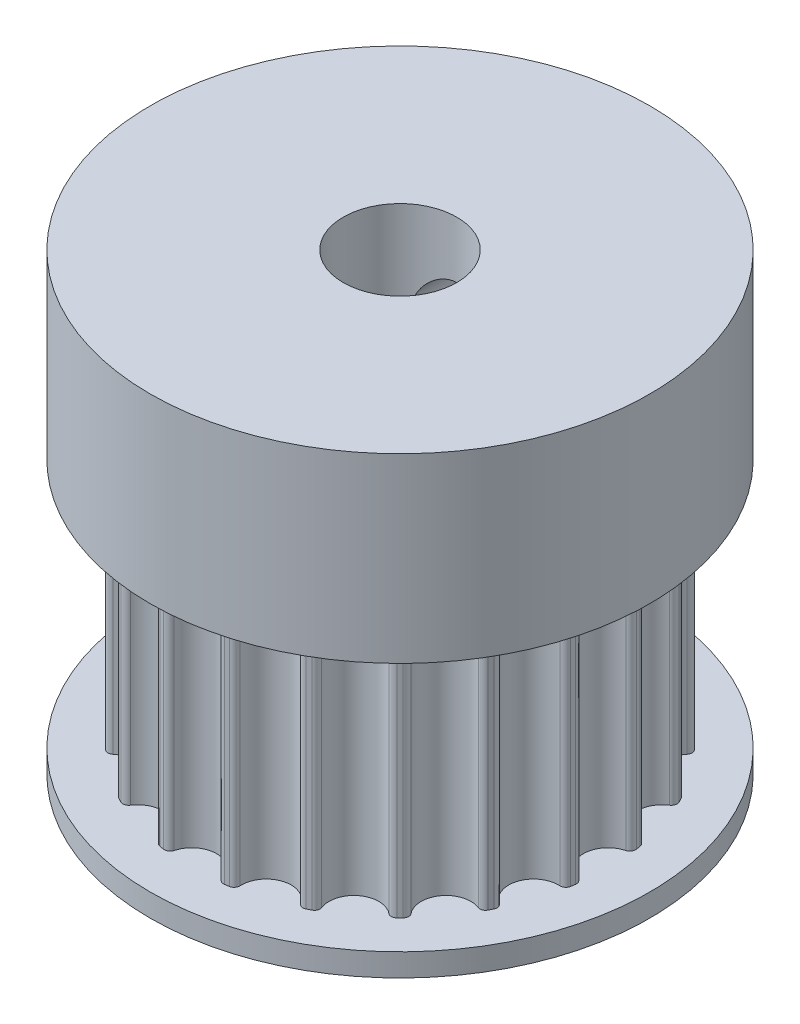
SolidWorks part; units mm, degrees
material "1060 合金"
ref_plane "前视基准面" through (0, 0, 0) normal (0, 0, 1) x (1, 0, 0)
ref_plane "上视基准面" through (0, 0, 0) normal (0, 1, 0) x (1, 0, 0)
ref_plane "右视基准面" through (0, 0, 0) normal (1, 0, 0) x (0, 0, -1)
other "Configuration Table"
sketch "草图1" plane through (0, 0, 0) normal (0, 1, 0) x (1, 0, 0)
  circle A0 centre (0, 0) radius 9.17
  dimension "D1" = 18.34
extrude "凸台-拉伸1" add sketch "草图1" against normal blind 11
sketch "草图2" plane through (0, 0, 0) normal (0, 1, 0) x (1, 0, 0)
  line L0 (0, -1000) -> (0, 49000) construction
  line L9 (-1.3385, 9.0718) -> (-1.302, 9.5481)
  line L10 (-1.302, 9.5481) -> (1.1645, 9.509)
  line L11 (1.1645, 9.509) -> (1.3385, 9.0718)
  arc A13 (-1.0603, 8.8886) -> (1.0603, 8.8886) centre (0, 9.17) ccw
  arc A14 (1.3385, 9.0718) -> (1.0603, 8.8886) centre (1.302, 8.8245) ccw
  arc A15 (-1.3385, 9.0718) -> (-1.0603, 8.8886) centre (-1.302, 8.8245) cw
extrude "切除-拉伸1" cut sketch "草图2" against normal blind 11
pattern_circular "阵列(圆周)1" count 20 over 360 about axis through (0, 0, 0) along (0, 1, 0) of "切除-拉伸1"
sketch "草图3" plane through (0, -11, 0) normal (0, -1, 0) x (1, 0, 0)
  circle A1 centre (0, 0) radius 11
sketch "草图4" plane through (0, 0, 0) normal (0, 1, 0) x (1, 0, 0)
  circle A0 centre (0, 0) radius 11
extrude "凸台-拉伸3" add sketch "草图4" along normal blind 8
extrude "凸台-拉伸4" add sketch "草图3" along normal blind 1
sketch "草图5" plane through (0, 8, 0) normal (0, 1, 0) x (1, 0, 0)
  circle A0 centre (0, 0) radius 2.5
extrude "切除-拉伸2" cut sketch "草图5" against normal blind 22
sketch "草图6" plane through (0, 0, 0) normal (0, 0, 1) x (1, 0, 0)
  line L1 (-11, 8) -> (-11, 0) construction
  circle A0 centre (0, 4) radius 1.5
  point P6 (-11, 4)
extrude "切除-拉伸3" cut sketch "草图6" against normal blind 30
